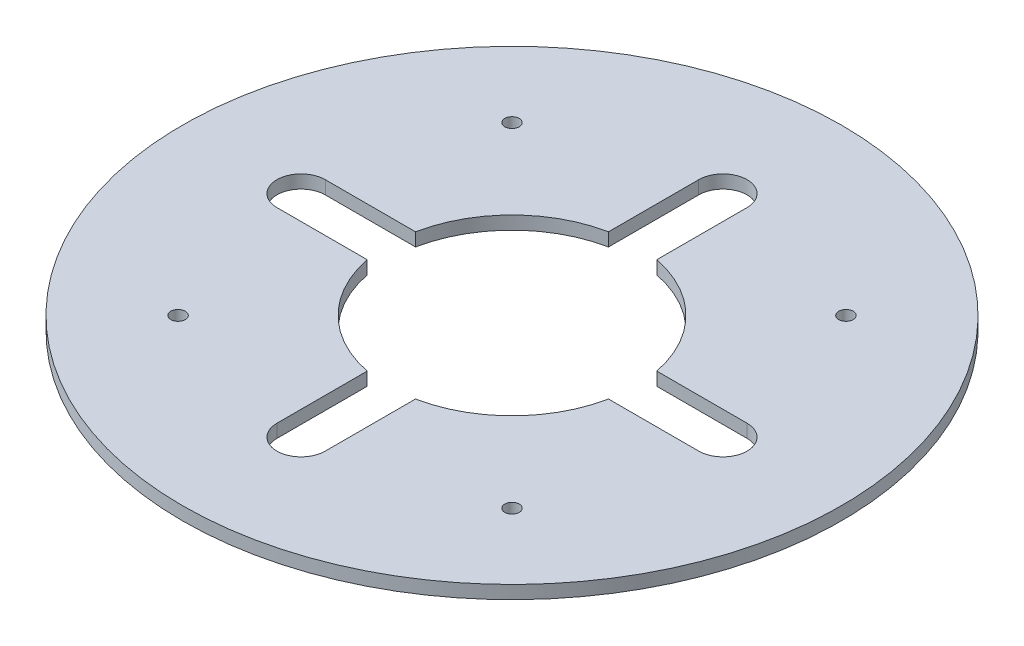
SolidWorks part; units mm, degrees
ref_plane "Front Plane" through (0, 0, 0) normal (0, 0, 1) x (1, 0, 0)
ref_plane "Top Plane" through (0, 0, 0) normal (0, 1, 0) x (1, 0, 0)
ref_plane "Right Plane" through (0, 0, 0) normal (1, 0, 0) x (0, 0, -1)
sketch "Sketch1" plane through (0, 0, 0) normal (0, 1, 0) x (1, 0, 0)
  circle A0 centre (0, 0) radius 75
  circle A1 centre (0, 0) radius 28
  dimension "D1" = 150
  dimension "D2" = 56
extrude "Boss-Extrude1" add sketch "Sketch1" along normal blind 3
sketch "Sketch2" plane through (0, 3, 0) normal (0, 1, 0) x (1, 0, 0)
  line L0 (-5.5, 48) -> (-5.5, 27.4545)
  line L1 (5.5, 48) -> (5.5, 27.4545)
  circle A0 centre (0, 48) radius 5.5
  circle A6 centre (0, 0) radius 28 construction
  arc A7 (-5.5, 27.4545) -> (5.5, 27.4545) centre (0, 27.4545) cw
  point P13 (0, 0)
  dimension "D2" = 11
  dimension "D1" = 48
extrude "Cut-Extrude2" cut sketch "Sketch2" against normal blind 3
pattern_circular "CirPattern1" count 4 over 360 about axis through (0, 0, 0) along (0, 1, 0) of "Cut-Extrude2"
hole_wizard "Tap Drill for M4x0.7 Tap1" positions "Sketch5" profile "Sketch6" hole size "M4x0.7" standard "ANSI Metric" end condition up to next
sketch "Sketch5" plane through (0, 3, 0) normal (0, 1, 0) x (1, 0, 0)
  arc A0 (5.5, 48) -> (-5.5, 48) centre (0, 48) ccw construction
  arc A1 (48, -5.5) -> (48, 5.5) centre (48, 0) ccw construction
  point P0 (38, 38)
  dimension "D1" = 10
  dimension "D2" = 10
sketch "Sketch6" plane through (38, 3, -38) normal (1, 0, 0) x (0, 0, 1)
  line L0 (0, 0) -> (0, 3.001)
  line L1 (0, 3.001) -> (1.65, 3.001)
  line L2 (1.65, 3.001) -> (1.65, 0)
  line L5 (1.65, 0) -> (0, 0)
  line L11 (0, -6.35) -> (0, 107.95) construction
  dimension "Thru Hole Dia." = 3.3
  dimension "Thru Hole Depth" = 3.001
pattern_circular "CirPattern2" count 4 over 360 about axis through (0, 0, 0) along (0, 1, 0) of "Tap Drill for M4x0.7 Tap1"
